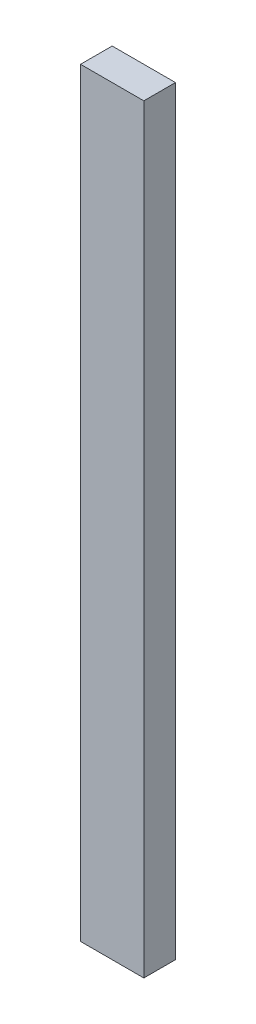
SolidWorks part; units mm, degrees
material "1060 Alloy"
ref_plane "Front Plane" through (0, 0, 0) normal (0, 0, 1) x (1, 0, 0)
ref_plane "Top Plane" through (0, 0, 0) normal (0, 1, 0) x (1, 0, 0)
ref_plane "Right Plane" through (0, 0, 0) normal (1, 0, 0) x (0, 0, -1)
sketch "Sketch1" plane through (0, 0, 0) normal (0, 0, 1) x (1, 0, 0)
  line L1 (-6.35, -76.2) -> (6.35, -76.2)
  line L2 (-6.35, -76.2) -> (-6.35, 76.2)
  line L3 (-6.35, 76.2) -> (6.35, 76.2)
  line L4 (6.35, -76.2) -> (6.35, 76.2)
  line L5 (-6.35, -76.2) -> (6.35, 76.2) construction
  line L6 (-6.35, 76.2) -> (6.35, -76.2) construction
  point P0 (0, 0)
  dimension "D1" = 12.7
  dimension "D2" = 152.4
extrude "Boss-Extrude1" add sketch "Sketch1" along normal blind 6.35
